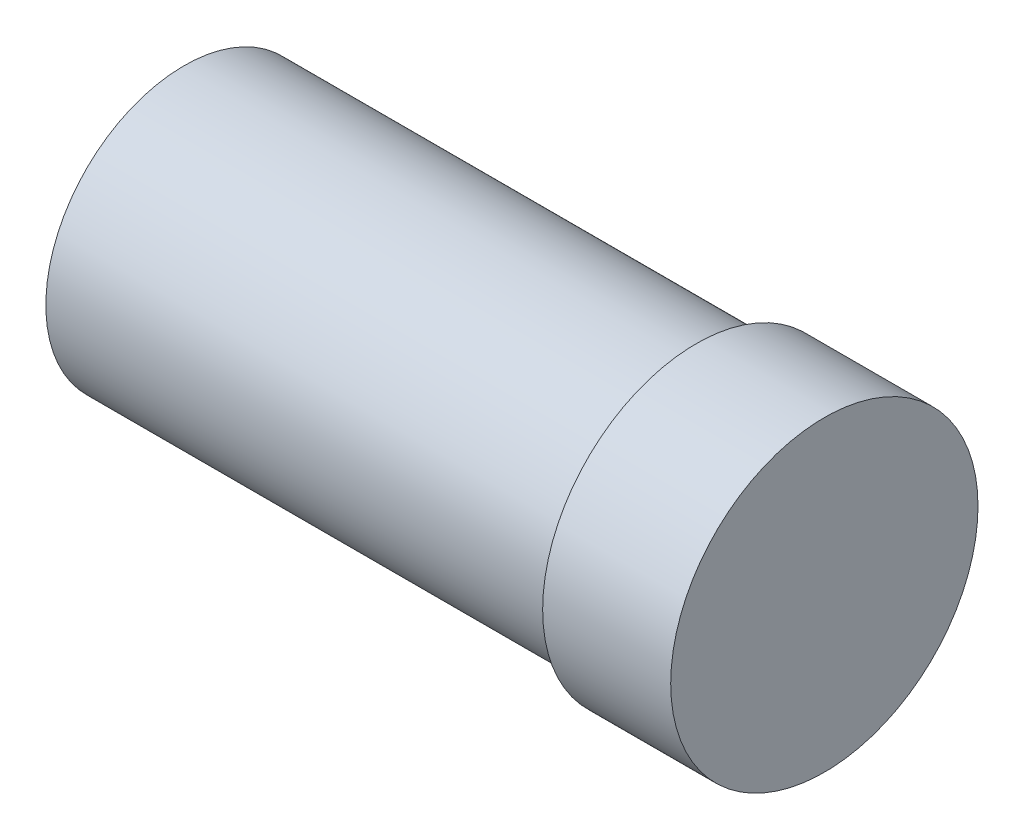
SolidWorks part; units mm, degrees
ref_plane "Front Plane" through (0, 0, 0) normal (0, 0, 1) x (1, 0, 0)
ref_plane "Top Plane" through (0, 0, 0) normal (0, 1, 0) x (1, 0, 0)
ref_plane "Right Plane" through (0, 0, 0) normal (1, 0, 0) x (0, 0, -1)
sketch "Sketch2" plane through (0, 0, 0) normal (1, 0, 0) x (0, 0, -1)
  circle A0 centre (0, 0) radius 27
extrude "Boss-Extrude1" add sketch "Sketch2" along normal blind 100
sketch "Sketch3" plane through (100, 0, 0) normal (1, 0, 0) x (0, 0, -1)
  circle A0 centre (0, 0) radius 30
extrude "Boss-Extrude2" add sketch "Sketch3" along normal blind 25
